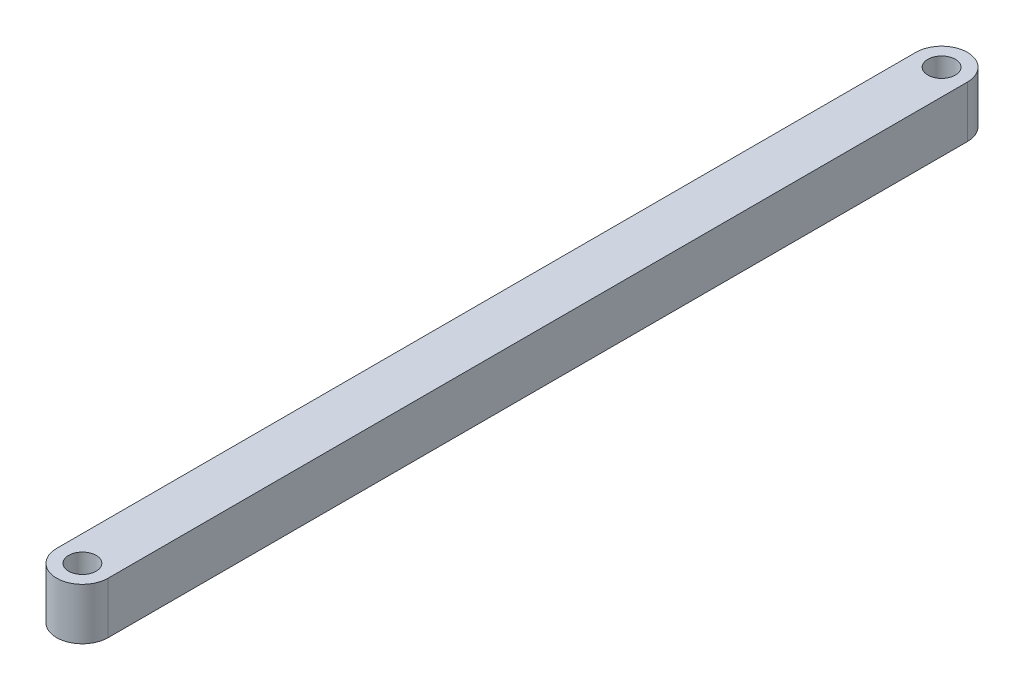
SolidWorks part; units mm, degrees
ref_plane "前视基准面" through (0, 0, 0) normal (0, 0, 1) x (1, 0, 0)
ref_plane "上视基准面" through (0, 0, 0) normal (0, 1, 0) x (1, 0, 0)
ref_plane "右视基准面" through (0, 0, 0) normal (1, 0, 0) x (0, 0, -1)
sketch "草图1" plane through (0, 0, 0) normal (0, 1, 0) x (1, 0, 0)
  line L0 (0, -50) -> (0, 50) construction
  line L1 (-3, -50) -> (-3, 50)
  line L2 (3, -50) -> (3, 50)
  arc A0 (-3, -50) -> (3, -50) centre (0, -50) ccw
  arc A1 (3, 50) -> (-3, 50) centre (0, 50) ccw
  circle A2 centre (0, 50) radius 1.6
  circle A3 centre (0, -50) radius 1.6
  point P2 (0, 0)
extrude "凸台-拉伸1" add sketch "草图1" along normal blind 6
